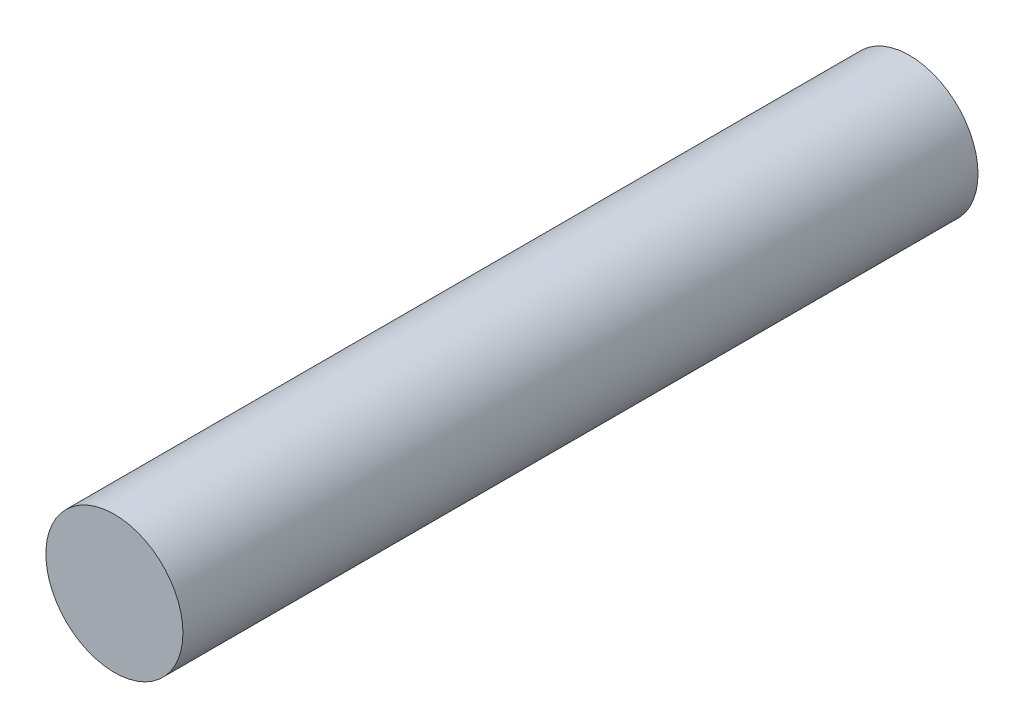
SolidWorks part; units mm, degrees
ref_plane "Front Plane" through (0, 0, 0) normal (0, 0, 1) x (1, 0, 0)
ref_plane "Top Plane" through (0, 0, 0) normal (0, 1, 0) x (1, 0, 0)
ref_plane "Right Plane" through (0, 0, 0) normal (1, 0, 0) x (0, 0, -1)
sketch "Sketch1" plane through (0, 0, 0) normal (0, 0, 1) x (1, 0, 0)
  circle A0 centre (0, 0) radius 3.175
  dimension "D1" = 6.35
extrude "Boss-Extrude1" add sketch "Sketch1" along normal blind 36.83
